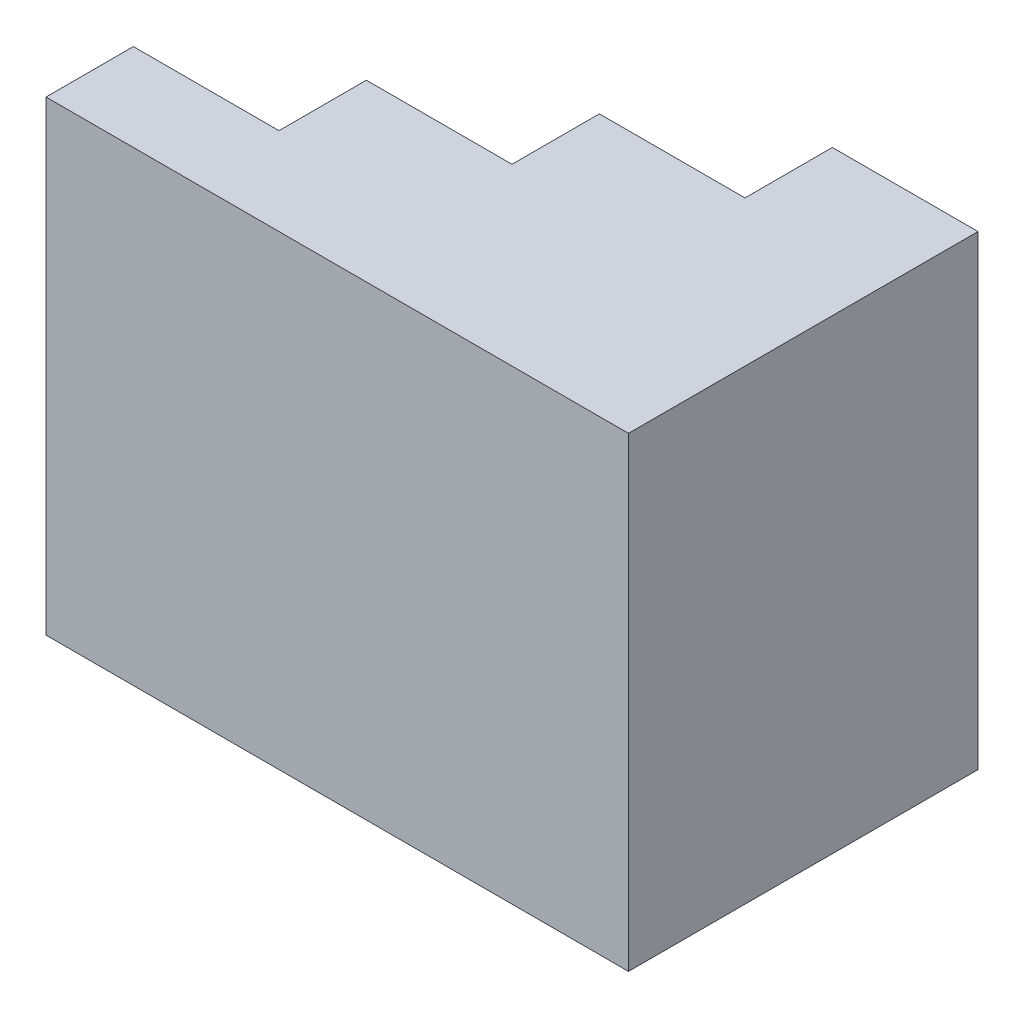
SolidWorks part; units mm, degrees
ref_plane "Front Plane" through (0, 0, 0) normal (0, 0, 1) x (1, 0, 0)
ref_plane "Top Plane" through (0, 0, 0) normal (0, 1, 0) x (1, 0, 0)
ref_plane "Right Plane" through (0, 0, 0) normal (1, 0, 0) x (0, 0, -1)
sketch "Sketch1" plane through (0, 0, 0) normal (0, 0, 1) x (1, 0, 0)
  line L5 (0, 0) -> (100, 0)
  line L6 (0, 0) -> (0, 80)
  line L7 (0, 80) -> (100, 80)
  line L8 (100, 0) -> (100, 80)
  dimension "D1" = 100
  dimension "D2" = 80
extrude "Boss-Extrude1" add sketch "Sketch1" along normal blind 60 contours L6 L7 L8 L5
sketch "Sketch5" plane through (0, 80, 0) normal (0, 1, 0) x (1, 0, 0)
  line L0 (0, 0) -> (75, 0)
  line L1 (0, 0) -> (100, 0) construction
  line L2 (75, 0) -> (75, -15)
  line L3 (75, -15) -> (50, -15)
  line L4 (50, -15) -> (50, -30)
  line L5 (50, -30) -> (25, -30)
  line L6 (25, -30) -> (25, -45)
  line L7 (25, -45) -> (0, -45)
  line L8 (0, -60) -> (0, 0) construction
  line L9 (0, -45) -> (0, 0)
  dimension "D1" = 15
  dimension "D2" = 25
extrude "Cut-Extrude2" cut sketch "Sketch5" against normal blind 60
